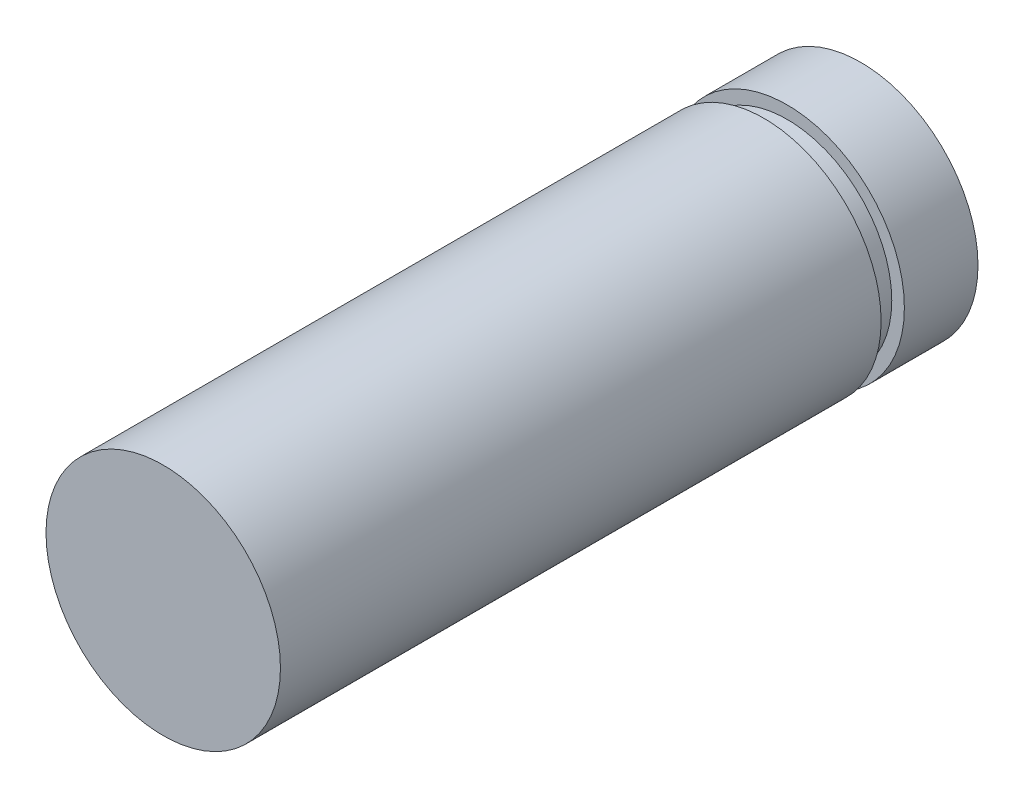
SolidWorks part; units mm, degrees
ref_plane "Front" through (0, 0, 0) normal (0, 0, 1) x (1, 0, 0)
ref_plane "Top" through (0, 0, 0) normal (0, 1, 0) x (1, 0, 0)
ref_plane "Right" through (0, 0, 0) normal (1, 0, 0) x (0, 0, -1)
sketch "Sketch1" plane through (0, 0, 0) normal (0, 0, 1) x (1, 0, 0)
  circle A0 centre (0, 0) radius 3.025
  dimension "D1" = 6.05
extrude "Boss-Extrude1" add sketch "Sketch1" along normal blind 18
ref_plane "Plane1" through (0, 0, 18) normal (-1, 0, 0) x (0, 1, 0)
sketch "Sketch3" plane through (0, 0, 18) normal (-1, 0, 0) x (0, 1, 0)
  line L0 (4.1, 15.5) -> (2.7, 15.5)
  line L1 (2.7, 15.5) -> (2.7, 16.1)
  line L2 (2.7, 16.1) -> (4.1, 16.1)
  line L3 (4.2, 16) -> (4.2, 15.6)
  line L4 (0, -50) -> (0, 50) construction
  line L5 (3.025, 18) -> (-3.025, 18) construction
  arc A0 (4.2, 15.6) -> (4.1, 15.5) centre (4.1, 15.6) cw
  arc A1 (4.2, 16) -> (4.1, 16.1) centre (4.1, 16) ccw
  dimension "D1" = 0.1
  dimension "D2" = 0.1
  dimension "D3" = 0.6
  dimension "D4" = 2.5
revolve "Groove for ANSI B27.7 - 3BM1-8, Basic Internal Retaining Ring1" cut sketch "Sketch3"
